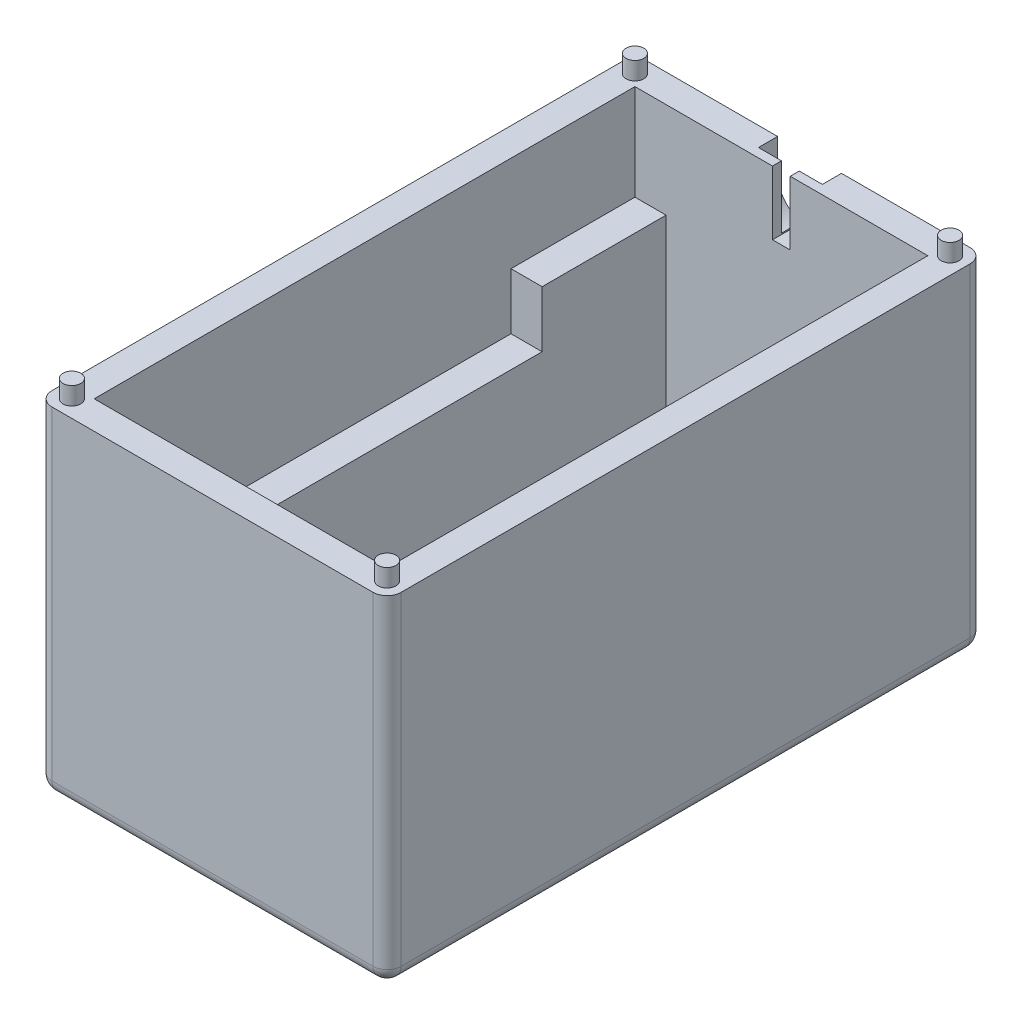
SolidWorks part; units mm, degrees
ref_plane "Front" through (0, 0, 0) normal (0, 0, 1) x (1, 0, 0)
ref_plane "Top" through (0, 0, 0) normal (0, 1, 0) x (1, 0, 0)
ref_plane "Right" through (0, 0, 0) normal (1, 0, 0) x (0, 0, -1)
sketch "Sketch1" plane through (0, 0, 0) normal (0, 1, 0) x (1, 0, 0)
  line L0 (-16.51, 30.48) -> (16.51, -30.48) construction
  line L1 (-16.51, -30.48) -> (16.51, -30.48)
  line L2 (-16.51, -30.48) -> (-16.51, 30.48)
  line L3 (-16.51, 30.48) -> (16.51, 30.48)
  line L4 (16.51, -30.48) -> (16.51, 30.48)
  point P6 (0, 0)
  dimension "D1" = 60.96
  dimension "D2" = 33.02
extrude "Base" add sketch "Sketch1" along normal blind 3.175 contours L1 L4 L3 L2 | L3 L0 L4
sketch "Sketch2" plane through (0, 3.175, 0) normal (0, 1, 0) x (1, 0, 0)
  line L3 (16.51, -30.48) -> (16.51, 30.48)
  line L4 (16.51, -30.48) -> (16.51, 30.48)
  line L5 (-13, 30.48) -> (13, 30.48)
  line L6 (-13, 30.48) -> (-13, -30.48)
  line L7 (-13, -30.48) -> (13, -30.48)
  line L8 (-16.51, -30.48) -> (16.51, -30.48)
  line L10 (16.51, 30.48) -> (-16.51, 30.48)
  line L11 (-16.51, 30.48) -> (-16.51, -30.48)
  line L12 (-16.51, -30.48) -> (16.51, -30.48)
  line L13 (16.51, 30.48) -> (-16.51, 30.48)
  line L15 (-16.51, 30.48) -> (-16.51, -30.48)
  line L16 (13, 30.48) -> (13, -30.48)
  point P3 (0, 30.48)
  point P8 (0, 30.48)
  line M8 (-16.51, -30.48) -> (16.51, -30.48)
  line M9 (16.51, -30.48) -> (16.51, 30.48)
  line M10 (16.51, 30.48) -> (-16.51, 30.48)
  line M11 (-16.51, 30.48) -> (-16.51, -30.48)
  dimension "D2" = 26
  dimension "D1" = 0
extrude "Battery-Sides" add sketch "Sketch2" along normal blind 17.78 contours L6 M10 M11 M8 | L16 M10 M8 M9
sketch "Sketch3" plane through (0, 0, 0) normal (0, -1, 0) x (1, 0, 0)
  line L7 (-19.685, -33.655) -> (19.685, -33.655)
  line L8 (19.685, 33.655) -> (-19.685, 33.655)
  line L9 (-19.685, 33.655) -> (-19.685, -33.655)
  line L10 (-19.685, -33.655) -> (19.685, -33.655)
  line L11 (-16.51, -30.48) -> (16.51, -30.48)
  line L12 (19.685, 33.655) -> (-19.685, 33.655)
  line L13 (-19.685, 33.655) -> (-19.685, -33.655)
  line L14 (-16.51, -30.48) -> (16.51, -30.48)
  line L16 (16.51, 30.48) -> (-16.51, 30.48)
  line L17 (-16.51, 30.48) -> (-16.51, -30.48)
  line L18 (19.685, -33.655) -> (19.685, 33.655)
  line L19 (19.685, -33.655) -> (19.685, 33.655)
  line L20 (16.51, 30.48) -> (-16.51, 30.48)
  line L21 (-16.51, 30.48) -> (-16.51, -30.48)
  line L22 (16.51, -30.48) -> (16.51, 30.48)
  line L23 (16.51, -30.48) -> (16.51, 30.48)
  dimension "D1" = 3.175
  dimension "D2" = 0
extrude "Outer-Casing" add sketch "Sketch3" against normal blind 38.1
sketch "Sketch4" plane through (0, 0, 0) normal (0, -1, 0) x (1, 0, 0)
  line L0 (19.685, 33.655) -> (-19.685, 33.655) construction
  line L1 (19.685, -33.655) -> (19.685, 33.655) construction
  circle A0 centre (0, 0) radius 10
  point P4 (0, 33.655)
  point P7 (19.685, 0)
  dimension "D1" = 20
extrude "Battery-push-hole" cut sketch "Sketch4" against normal up to next
fillet "Fillet1" radius 1.5875 9 edges at (0, 0, -33.655) (-19.685, 0, 0) (0, 0, 33.655) (19.685, 0, 0) (0, 0, -10) (19.685, 19.05, 33.655) (19.685, 19.05, -33.655) (-19.685, 19.05, -33.655) (-19.685, 19.05, 33.655)
sketch "Sketch5" plane through (0, 38.1, 0) normal (0, 1, 0) x (1, 0, 0)
  line L0 (-19.22, 33.19) -> (-16.51, 30.48) construction
  line L1 (0, 33.655) -> (0, -33.655) construction
  line L2 (-18.0975, 33.655) -> (18.0975, 33.655) construction
  line L3 (18.0975, -33.655) -> (-18.0975, -33.655) construction
  line L5 (-19.685, -32.0675) -> (-19.685, 32.0675) construction
  line L6 (-19.685, 0) -> (19.685, 0) construction
  line L7 (19.685, 32.0675) -> (19.685, -32.0675) construction
  circle A0 centre (-17.7672, 31.7372) radius 1
  circle A1 centre (-17.7672, -31.7372) radius 1
  circle A2 centre (17.7672, 31.7372) radius 1
  circle A3 centre (17.7672, -31.7372) radius 1
  arc A4 (-18.0975, 33.655) -> (-19.685, 32.0675) centre (-18.0975, 32.0675) ccw construction
  dimension "D1" = 2
  dimension "D2" = 1.778
extrude "Alignment Pegs" add sketch "Sketch5" along normal blind 2
sketch "Sketch6" plane through (0, 0, -33.655) normal (0, 0, -1) x (-1, 0, 0)
  line L0 (-1, 38.1) -> (1, 30.9) construction
  line L1 (-1, 38.1) -> (1, 38.1)
  line L2 (-1, 38.1) -> (-1, 30.9)
  line L3 (-1, 30.9) -> (1, 30.9)
  line L4 (1, 38.1) -> (1, 30.9)
  line L6 (18.0975, 38.1) -> (-18.0975, 38.1) construction
  circle A0 centre (0, 34.5) radius 3.6 construction
  point P2 (0, 34.5)
  dimension "D1" = 7.2
  dimension "D2" = 2
extrude "Attachment Narrow Point" cut sketch "Sketch6" against normal up to next
sketch "Sketch8" plane through (0, 0, -33.655) normal (0, 0, 1) x (1, 0, 0)
  line L0 (-1, 38.1) -> (1, 30.9) construction
  line L1 (-1, 38.1) -> (1, 38.1) construction
  line L2 (-1, 38.1) -> (-1, 30.9) construction
  line L3 (-1, 30.9) -> (1, 30.9) construction
  line L4 (1, 38.1) -> (1, 30.9) construction
  line L5 (16.51, 38.1) -> (-16.51, 38.1) construction
  line L7 (-18.0975, 38.1) -> (-1, 38.1) construction
  line L9 (3.6, 34.5) -> (3.6, 38.1)
  line L10 (3.6, 38.1) -> (-3.6, 38.1)
  line L11 (-3.6, 34.5) -> (-3.6, 38.1)
  arc A0 (1, 37.9583) -> (-1, 37.9583) centre (0, 34.5) ccw
  arc A1 (-3.6, 34.5) -> (3.6, 34.5) centre (0, 34.5) ccw
  point P2 (0, 34.5)
  line M16 (1, 30.9) -> (1, 38.1)
  line M17 (1, 38.1) -> (18.0975, 38.1)
  line M21 (-18.0975, 38.1) -> (-1, 38.1)
  line M22 (-1, 38.1) -> (-1, 30.9)
  dimension "D1" = 7.2
  dimension "D2" = 2
extrude "Cut-Extrude4" cut sketch "Sketch8" along normal blind 2.157 contours A1 L9 M16 M17 | A1 L11 M21 M22
sketch "Sketch9" plane through (0, 20.955, 0) normal (0, 1, 0) x (1, 0, 0)
  line L0 (16.51, 30.48) -> (16.51, -30.48) construction
  line L1 (-16.51, 30.48) -> (-13, 30.48)
  line L2 (-16.51, 30.48) -> (-16.51, 16.51)
  line L3 (-16.51, 16.51) -> (-13, 16.51)
  line L4 (16.51, 30.48) -> (16.51, 16.51)
  line L5 (16.51, 30.48) -> (13, 30.48) construction
  line L6 (13, 30.48) -> (13, -30.48) construction
  line L7 (13, -30.48) -> (16.51, -30.48) construction
  line L8 (16.51, -30.48) -> (16.51, 30.48) construction
  line L9 (-13, -30.48) -> (-13, 30.48) construction
  line L10 (-13, 30.48) -> (-16.51, 30.48) construction
  line L11 (-16.51, 30.48) -> (-16.51, -30.48) construction
  line L12 (-16.51, -30.48) -> (-13, -30.48) construction
  line L13 (16.51, 30.48) -> (13, 30.48)
  line L14 (13, 30.48) -> (13, -30.48)
  line L15 (13, -30.48) -> (16.51, -30.48)
  line L16 (16.51, -30.48) -> (16.51, 30.48)
  line L17 (-13, -30.48) -> (-13, 30.48)
  line L18 (-13, 30.48) -> (-16.51, 30.48)
  line L19 (-16.51, 30.48) -> (-16.51, -30.48)
  line L20 (-16.51, -30.48) -> (-13, -30.48)
  line L21 (13, 16.51) -> (16.51, 16.51)
  line L22 (13, 30.48) -> (16.51, 30.48)
  line M3 (-13, -30.48) -> (-13, 30.48)
  line M4 (-13, 30.48) -> (-16.51, 30.48)
  line M5 (-16.51, 30.48) -> (-16.51, -30.48)
  dimension "D1" = 46.99
extrude "Boss-Extrude5" add sketch "Sketch9" along normal blind 6.35 contours L3 M5 M3 M4 | L14 L21 L4 L13
